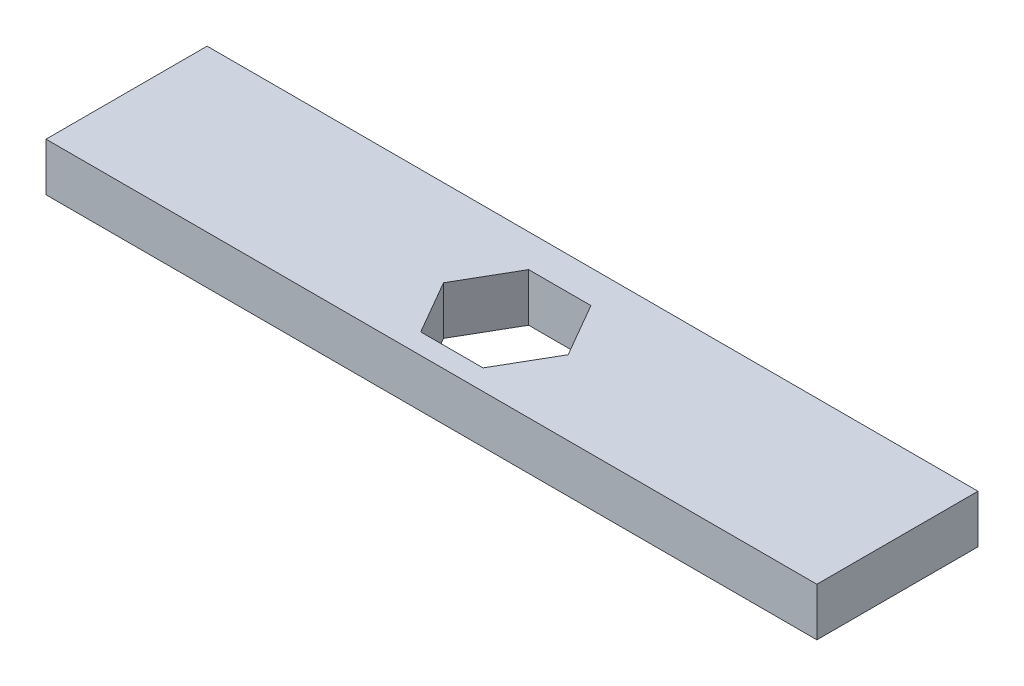
SolidWorks part; units mm, degrees
ref_plane "Ebene vorne" through (0, 0, 0) normal (0, 0, 1) x (1, 0, 0)
ref_plane "Ebene oben" through (0, 0, 0) normal (0, 1, 0) x (1, 0, 0)
ref_plane "Ebene rechts" through (0, 0, 0) normal (1, 0, 0) x (0, 0, -1)
sketch "Skizze1" plane through (0, 0, 0) normal (0, 1, 0) x (1, 0, 0)
  line L0 (0, 0) -> (40, 0)
  line L1 (-55, 0) -> (55, 0) construction
  line L2 (40, 0) -> (40, 8.36)
  line L3 (40, 8.36) -> (0, 8.36)
  line L4 (0, -55) -> (0, 55) construction
  line L5 (0, 8.36) -> (0, 0)
  dimension "D1" = 8.36
  dimension "D2" = 40
extrude "Aufsatz-Linear austragen1" add sketch "Skizze1" along normal blind 2.5
sketch "Skizze3" plane through (0, 2.5, 0) normal (0, 1, 0) x (1, 0, 0)
  line L1 (23.2332, 3.86) -> (21.6166, 6.66)
  line L2 (21.6166, 6.66) -> (18.3834, 6.66)
  line L3 (18.3834, 6.66) -> (16.7668, 3.86)
  line L4 (16.7668, 3.86) -> (18.3834, 1.06)
  line L5 (18.3834, 1.06) -> (21.6166, 1.06)
  line L6 (21.6166, 1.06) -> (23.2332, 3.86)
  line L7 (0, -1.375) -> (0, 1.375) construction
  line L10 (40, 8.36) -> (0, 8.36) construction
  circle A0 centre (20, 3.86) radius 2.8 construction
  dimension "D1" = 5.6
  dimension "D2" = 4.5
  dimension "D3" = 20
extrude "Schnitt-Linear austragen1" cut sketch "Skizze3" against normal up to surface (2.5 mm away) up to face at (20, 0, -4.18)
